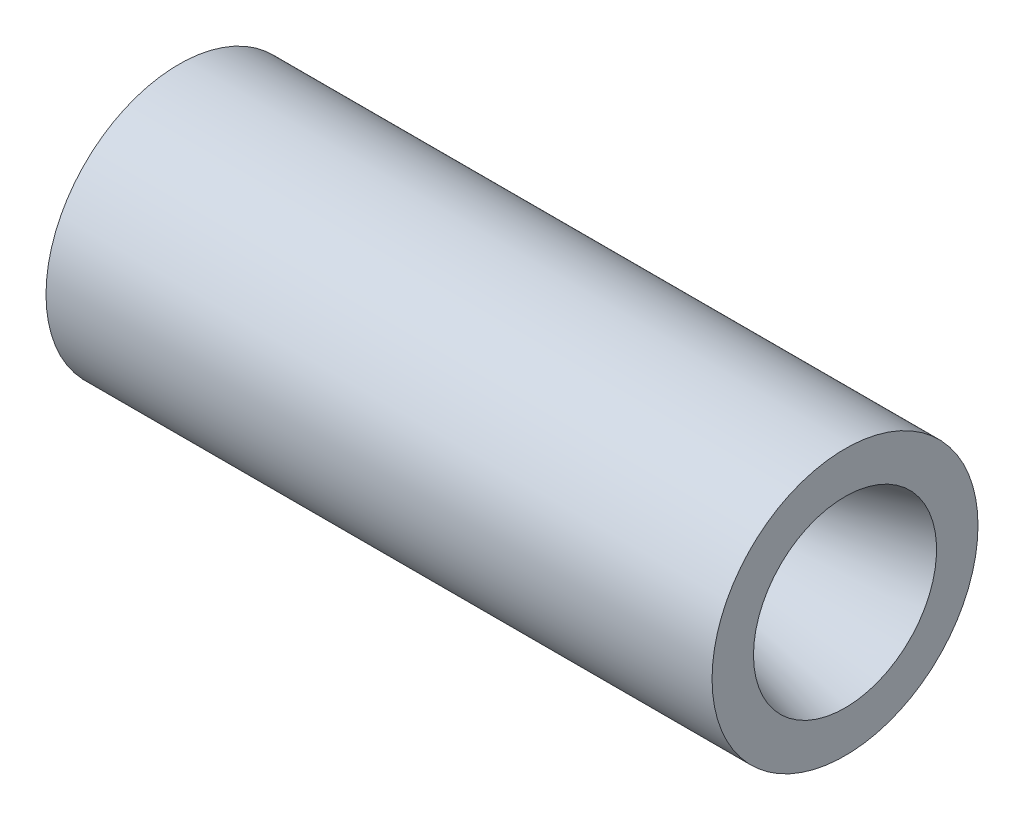
SolidWorks part; units mm, degrees
ref_plane "Front Plane" through (0, 0, 0) normal (0, 0, 1) x (1, 0, 0)
ref_plane "Top Plane" through (0, 0, 0) normal (0, 1, 0) x (1, 0, 0)
ref_plane "Right Plane" through (0, 0, 0) normal (1, 0, 0) x (0, 0, -1)
sketch "Sketch1" plane through (0, 0, 0) normal (0, 0, 1) x (1, 0, 0)
  line L0 (0, 0) -> (267.1743, 0) construction
  line L1 (267.1743, 0) -> (267.1743, 36.7237) construction
  line L2 (0, 43.2766) -> (0, 0) construction
  line L3 (0, 53.34) -> (267.1743, 53.34)
  line L4 (0, 53.34) -> (0, 43.2766)
  line L6 (152.7031, 40.2068) -> (181.4981, 20.0443)
  line L7 (195.6276, 17.5529) -> (267.1743, 36.7237)
  line L8 (267.1743, 36.7237) -> (267.1743, 53.34)
  line L9 (125.6605, 16.9745) -> (331.7289, 16.9745) construction
  line L10 (0, 43.2766) -> (142.9669, 43.2766)
  arc A1 (195.6276, 17.5529) -> (181.4981, 20.0443) centre (191.2343, 33.9489) cw
  arc A2 (152.7031, 40.2068) -> (142.9669, 43.2766) centre (142.9669, 26.3021) ccw
  point P14 (187.982, 15.5042)
  point P26 (148.3189, 43.2766)
  dimension "D2" = 16.9745
  dimension "D3" = 15
  dimension "D4" = 35
  dimension "D1" = 16.9745
  dimension "D5" = 53.34
  dimension "D6" = 43.2766
  dimension "D8" = 36.7237
  dimension "D7" = 142.9669
revolve "Revolve1" add sketch "Sketch1" angle 360 about L0
equation "\"D5@Sketch1\"=4.5/2-(.15)"
equation "\"D2@Sketch1\"=\"D1@Sketch1\""
equation "\"D6@Sketch1\"=3.407604/2"
equation "\"D8@Sketch1\"=2.891633/2"
equation "\"D1@Sketch1\"=1.336572235/2"
